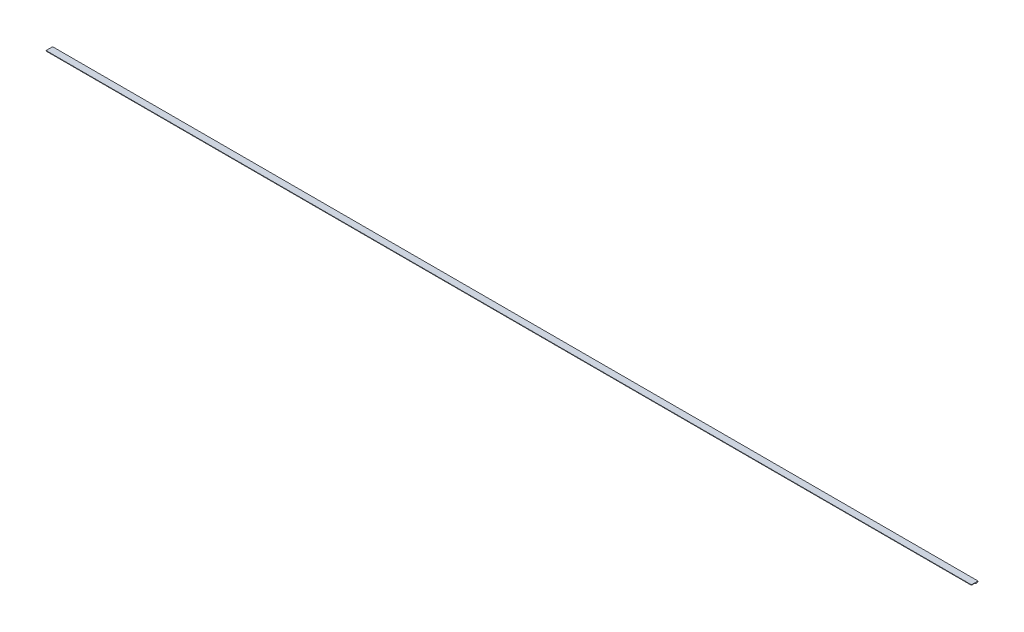
SolidWorks part; units mm, degrees
ref_plane "Front Plane" through (0, 0, 0) normal (0, 0, 1) x (1, 0, 0)
ref_plane "Top Plane" through (0, 0, 0) normal (0, 1, 0) x (1, 0, 0)
ref_plane "Right Plane" through (0, 0, 0) normal (1, 0, 0) x (0, 0, -1)
sketch "Sketch1" plane through (0, 0, 0) normal (1, 0, 0) x (0, 0, -1)
  line L0 (-28.474, 0) -> (-17.474, 0)
  line L1 (-28.474, 0) -> (-28.474, -0.7594)
  line L2 (-28.474, -0.7594) -> (-23.1999, -0.7594)
  line L5 (-17.474, -0.7594) -> (-17.474, 0)
  ellipse E0 centre (-20.3369, -0.7594) end of major axis (-19.3317, -0.7594) minor radius 0.3872
  spline S0 degree 2 poles (-17.474, -0.7594) (-20.3369, -3.3945) (-23.1999, -0.7594) knots 0 0 0 1 1 1
  dimension "D1" = 11
extrude "Boss-Extrude1" add sketch "Sketch1" along normal blind 1540
